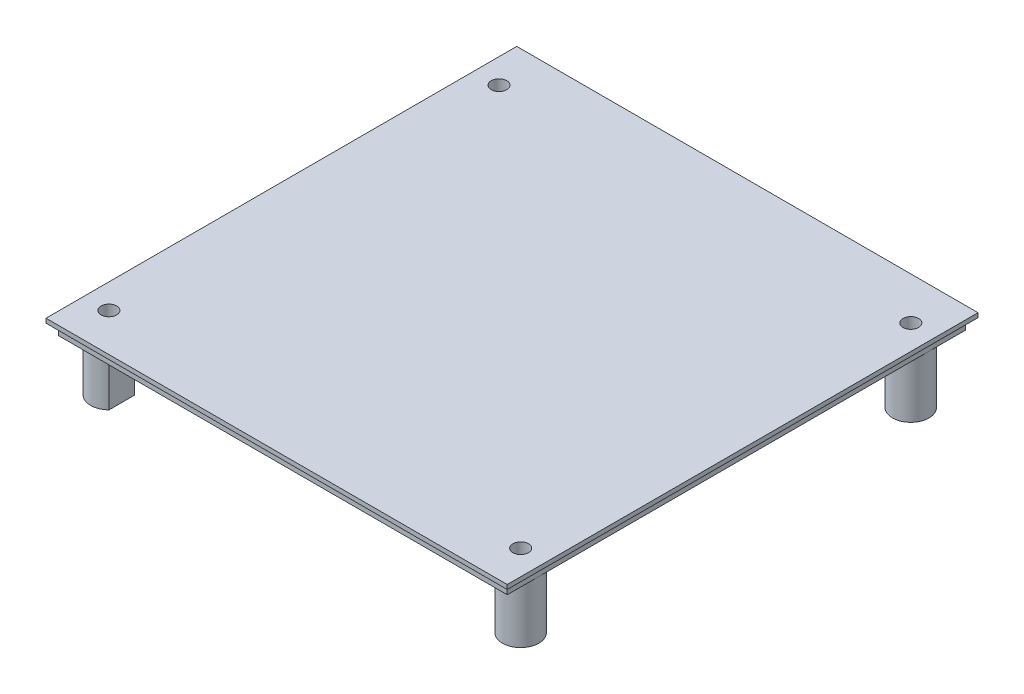
SolidWorks part; units mm, degrees
ref_plane "前视基准面" through (0, 0, 0) normal (0, 0, 1) x (1, 0, 0)
ref_plane "上视基准面" through (0, 0, 0) normal (0, 1, 0) x (1, 0, 0)
ref_plane "右视基准面" through (0, 0, 0) normal (1, 0, 0) x (0, 0, -1)
sketch "草图1" plane through (0, 0, 0) normal (0, 1, 0) x (1, 0, 0)
  line L1 (-53.2, 54.3) -> (53.2, 54.3)
  line L2 (-53.2, 54.3) -> (-53.2, -54.3)
  line L3 (-53.2, -54.3) -> (53.2, -54.3)
  line L4 (53.2, 54.3) -> (53.2, -54.3)
  line L5 (-53.2, 54.3) -> (53.2, -54.3) construction
  line L6 (-53.2, -54.3) -> (53.2, 54.3) construction
  point P0 (0, 0)
  dimension "D1" = 106.4
  dimension "D2" = 108.6
extrude "凸台-拉伸1" add sketch "草图1" along normal blind 1
sketch "草图2" plane through (0, 0, 0) normal (0, -1, 0) x (1, 0, 0)
  line L0 (51.75, -52.85) -> (51.75, 52.85)
  line L1 (51.75, 52.85) -> (-51.75, 52.85)
  line L2 (-51.75, 52.85) -> (-51.75, -52.85)
  line L3 (-51.75, -52.85) -> (51.75, -52.85)
  line L4 (53.2, -54.3) -> (53.2, 54.3)
  line L5 (53.2, 54.3) -> (-53.2, 54.3)
  line L6 (-53.2, 54.3) -> (-53.2, -54.3)
  line L7 (-53.2, -54.3) -> (53.2, -54.3)
  line L8 (53.2, -54.3) -> (53.2, 54.3) construction
  line L9 (53.2, 54.3) -> (-53.2, 54.3) construction
  line L10 (-53.2, 54.3) -> (-53.2, -54.3) construction
  line L11 (-53.2, -54.3) -> (53.2, -54.3) construction
  line L12 (51.05, -52.15) -> (51.05, 52.15)
  line L13 (51.05, 52.15) -> (-51.05, 52.15)
  line L14 (-51.05, 52.15) -> (-51.05, -52.15)
  line L15 (-51.05, -52.15) -> (51.05, -52.15)
  dimension "D1" = 0
  dimension "D2" = 1.45
  dimension "D3" = 0.7
extrude "凸台-拉伸2" add sketch "草图2" along normal blind 2.5
sketch "草图4" plane through (0, 1, 0) normal (0, 1, 0) x (1, 0, 0)
  circle A0 centre (47.5, 44.5) radius 1.7 construction
  circle A1 centre (-47.5, 44.5) radius 1.7 construction
  circle A2 centre (-47.5, -45.5) radius 1.7 construction
  circle A3 centre (47.5, -45.5) radius 1.7 construction
  circle A4 centre (47.5, 44.5) radius 1.7 construction
  circle A5 centre (-47.5, 44.5) radius 1.7 construction
  circle A6 centre (-47.5, -45.5) radius 1.7 construction
  circle A7 centre (47.5, -45.5) radius 1.7 construction
  circle A8 centre (47.5, 44.5) radius 1.8
  circle A9 centre (-47.5, 44.5) radius 1.8
  circle A10 centre (-47.5, -45.5) radius 1.8
  circle A11 centre (47.5, -45.5) radius 1.8
  dimension "D1" = 0.1
extrude "切除-拉伸1" cut sketch "草图4" against normal through all
sketch "草图5" plane through (0, 0, 0) normal (0, -1, 0) x (1, 0, 0)
  line L0 (51.05, 52.15) -> (-51.05, 52.15) construction
  line L1 (-0.4, 52.15) -> (0.4, 52.15)
  line L2 (-0.4, 52.15) -> (-0.4, -52.15)
  line L3 (-0.4, -52.15) -> (0.4, -52.15)
  line L4 (0.4, 52.15) -> (0.4, -52.15)
  line L6 (-51.05, -52.15) -> (51.05, -52.15) construction
  line L7 (51.05, -52.15) -> (51.05, 52.15) construction
  line L8 (-51.05, 0.4) -> (51.05, 0.4)
  line L9 (-51.05, 0.4) -> (-51.05, -0.4)
  line L10 (-51.05, -0.4) -> (51.05, -0.4)
  line L11 (51.05, 0.4) -> (51.05, -0.4)
  line L12 (-51.05, 0.4) -> (51.05, -0.4) construction
  line L13 (-51.05, -0.4) -> (51.05, 0.4) construction
  point P10 (0, -52.15)
  point P12 (0, 0)
  line M12 (-51.05, 52.15) -> (-51.05, -52.15)
  dimension "D1" = 0.8
  dimension "D2" = 0.8
extrude "凸台-拉伸3" [suppressed] add sketch "草图5" along normal up to surface (2.5 mm away) contours L10 L2 L8 M12
fillet "圆角1" [suppressed] radius 1
fillet "圆角2" [suppressed] radius 0.5
chamfer "倒角1" [suppressed] distance 1 angle 45
sketch "草图6" [suppressed] plane through (51.85, 0, 0) normal (1, 0, 0) x (0, 0, -1)
  line L2 (-54.3, 0) -> (-54.3, 1) construction
  line L3 (-53.3, 1) -> (53.3, 1) construction
  line L4 (0, -2.5) -> (0, 13.1025) construction
  line L5 (52.45, -2.5) -> (-52.45, -2.5) construction
  circle A4 centre (-41.3, -2) radius 0.95
  circle A6 centre (-41.3, -2) radius 2
  circle A7 centre (41.3, -2) radius 2
  circle A8 centre (41.3, -2) radius 0.95
  dimension "D1" = 1.9
  dimension "D2" = 13
  dimension "D3" = 3
  dimension "D4" = 4
extrude "凸台-拉伸4" [suppressed] add sketch "草图6" against normal up to surface (0.8 mm away)
sketch "草图7" [suppressed] plane through (-51.85, 0, 0) normal (-1, 0, 0) x (0, 0, 1)
  circle A1 centre (-41.3, -2) radius 0.95
  circle A2 centre (-41.3, -2) radius 0.95
  circle A3 centre (-41.3, -2) radius 2
  circle A4 centre (-41.3, -2) radius 2
  circle A5 centre (41.3, -2) radius 2
  circle A6 centre (41.3, -2) radius 2
  circle A7 centre (41.3, -2) radius 0.95
  circle A8 centre (41.3, -2) radius 0.95
  dimension "D1" = 0
  dimension "D2" = 0
  dimension "D3" = 0
  dimension "D4" = 0
extrude "凸台-拉伸5" [suppressed] add sketch "草图7" against normal up to surface (0.8 mm away)
sketch "草图8" [suppressed] plane through (51.85, 0, 0) normal (1, 0, 0) x (0, 0, -1)
  circle A1 centre (41.3, -2) radius 0.95
  circle A2 centre (41.3, -2) radius 0.95
  circle A7 centre (-41.3, -2) radius 0.95
  circle A8 centre (-41.3, -2) radius 0.95
  dimension "D1" = 0
  dimension "D4" = 0
extrude "切除-拉伸2" [suppressed] cut sketch "草图8" against normal up to surface (0.8 mm away)
sketch "草图9" [suppressed] plane through (-51.85, 0, 0) normal (-1, 0, 0) x (0, 0, 1)
  circle A1 centre (41.3, -2) radius 0.95
  circle A2 centre (41.3, -2) radius 0.95
  circle A7 centre (-41.3, -2) radius 0.95
  circle A8 centre (-41.3, -2) radius 0.95
  dimension "D1" = 0
  dimension "D4" = 0
extrude "切除-拉伸3" [suppressed] cut sketch "草图9" against normal up to surface (0.8 mm away)
fillet "圆角3" [suppressed] radius 1
sketch "草图10" [suppressed] plane through (-51.85, 0, 0) normal (-1, 0, 0) x (0, 0, 1)
  line L0 (52.45, 0) -> (-52.45, 0) construction
  line L2 (-43.3, -2) -> (-43.3, 0)
  line L3 (-43.3, 0) -> (-39.3, 0)
  line L4 (-39.3, -2) -> (-39.3, 0)
  line L5 (0, 0) -> (0, 14.2096) construction
  line L6 (39.3, -2) -> (39.3, 0)
  line L7 (43.3, 0) -> (39.3, 0)
  line L8 (43.3, -2) -> (43.3, 0)
  circle A0 centre (41.3, -2) radius 0.95
  arc A1 (43.3, -2) -> (39.3, -2) centre (41.3, -2) cw
  circle A5 centre (-41.3, -2) radius 2
  arc A6 (-43.3, -2) -> (-39.3, -2) centre (-41.3, -2) ccw
  circle A7 centre (-41.3, -2) radius 0.95
  circle A8 centre (-41.3, -2) radius 0.95
  dimension "D3" = 0
  dimension "D4" = 0
extrude "凸台-拉伸6" [suppressed] add sketch "草图10" against normal blind 3
sketch "草图11" [suppressed] plane through (51.85, 0, 0) normal (1, 0, 0) x (0, 0, -1)
  line L3 (-39.3, -2) -> (-39.3, 0)
  line L4 (-39.3, 0) -> (-43.3, 0)
  line L5 (-43.3, 0) -> (-43.3, -2)
  line L6 (-39.3, -2) -> (-39.3, 0)
  line L7 (-39.3, 0) -> (-43.3, 0)
  line L8 (-43.3, 0) -> (-43.3, -2)
  line L9 (43.3, -2) -> (43.3, 0)
  line L10 (43.3, 0) -> (39.3, 0)
  line L11 (39.3, 0) -> (39.3, -2)
  line L12 (43.3, -2) -> (43.3, 0)
  line L13 (43.3, 0) -> (39.3, 0)
  line L14 (39.3, 0) -> (39.3, -2)
  circle A1 centre (41.3, -2) radius 0.95
  circle A2 centre (41.3, -2) radius 0.95
  circle A3 centre (-41.3, -2) radius 0.95
  circle A4 centre (-41.3, -2) radius 0.95
  arc A5 (-43.3, -2) -> (-39.3, -2) centre (-41.3, -2) ccw
  arc A6 (-43.3, -2) -> (-39.3, -2) centre (-41.3, -2) ccw
  arc A7 (39.3, -2) -> (43.3, -2) centre (41.3, -2) ccw
  arc A8 (39.3, -2) -> (43.3, -2) centre (41.3, -2) ccw
  dimension "D1" = 0
  dimension "D2" = 0
  dimension "D3" = 0
  dimension "D4" = 0
extrude "凸台-拉伸7" [suppressed] add sketch "草图11" against normal blind 3
sketch "草图13" plane through (0, 0, 0) normal (0, -1, 0) x (1, 0, 0)
  circle A0 centre (-47.5, 45.5) radius 4.2
  circle A1 centre (47.5, 45.5) radius 4.2
  circle A2 centre (-47.5, -44.5) radius 4.2
  circle A3 centre (47.5, -44.5) radius 4.2
  circle A4 centre (-47.5, 45.5) radius 1.8 construction
  circle A5 centre (-47.5, 45.5) radius 1.8
  circle A6 centre (47.5, 45.5) radius 1.8 construction
  circle A7 centre (47.5, 45.5) radius 1.8
  circle A8 centre (47.5, -44.5) radius 1.8 construction
  circle A9 centre (47.5, -44.5) radius 1.8
  circle A10 centre (-47.5, -44.5) radius 1.8 construction
  circle A11 centre (-47.5, -44.5) radius 1.8
  dimension "D1" = 8.4
extrude "凸台-拉伸8" add sketch "草图13" along normal blind 15.89
sketch "草图14" plane through (0, -15.89, 0) normal (0, -1, 0) x (1, 0, 0)
  line L1 (-44.5, 50.7246) -> (44.5, 50.7246)
  line L2 (-44.5, 50.7246) -> (-44.5, -50.7246)
  line L3 (-44.5, -50.7246) -> (44.5, -50.7246)
  line L4 (44.5, 50.7246) -> (44.5, -50.7246)
  line L5 (-44.5, 50.7246) -> (44.5, -50.7246) construction
  line L6 (-44.5, -50.7246) -> (44.5, 50.7246) construction
  point P0 (0, 0)
  dimension "D1" = 89
extrude "切除-拉伸6" cut sketch "草图14" against normal up to surface (15.89 mm away) up to face at (0, 0, 0.3333)
